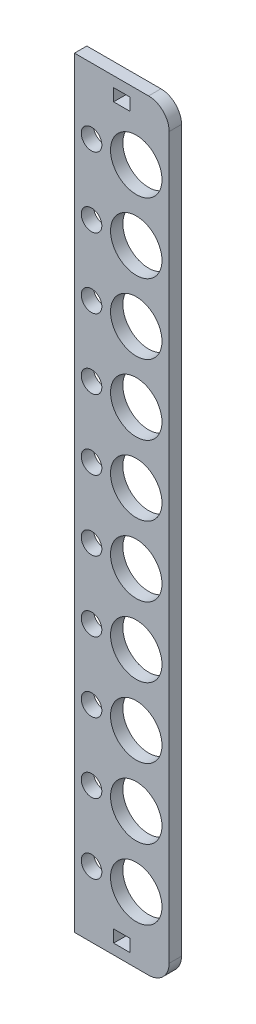
SolidWorks part; units mm, degrees
ref_plane "Plan de face" through (0, 0, 0) normal (0, 0, 1) x (1, 0, 0)
ref_plane "Plan de dessus" through (0, 0, 0) normal (0, 1, 0) x (1, 0, 0)
ref_plane "Plan de droite" through (0, 0, 0) normal (1, 0, 0) x (0, 0, -1)
sketch "Esquisse1" plane through (0, 0, 0) normal (0, 0, 1) x (1, 0, 0)
  line L0 (0, 185) -> (46, 185) construction
  line L1 (0, 0) -> (46, 0)
  line L2 (0, 0) -> (0, 370)
  line L3 (0, 370) -> (46, 370)
  line L4 (46, 0) -> (46, 370)
  line L5 (19, 5) -> (27, 5)
  line L6 (19, 5) -> (19, 11)
  line L7 (19, 11) -> (27, 11)
  line L8 (27, 5) -> (27, 11)
  line L9 (27, 365) -> (27, 359)
  line L10 (19, 359) -> (27, 359)
  line L11 (19, 365) -> (19, 359)
  line L12 (19, 365) -> (27, 365)
  dimension "D1" = 370
  dimension "D2" = 46
  dimension "D3" = 8
  dimension "D4" = 6
  dimension "D5" = 5
  dimension "D6" = 19
extrude "Boss.-Extru.1" add sketch "Esquisse1" along normal blind 6
sketch "Esquisse2" plane through (0, 0, 6) normal (0, 0, 1) x (1, 0, 0)
  line L0 (0, 370) -> (0, 0) construction
  line L1 (0, 0) -> (46, 0) construction
  line L2 (46, 0) -> (46, 370) construction
  line L3 (46, 370) -> (0, 370) construction
  circle A0 centre (30, 32) radius 12.5
  circle A1 centre (30, 66) radius 12.5
  circle A2 centre (30, 100) radius 12.5
  circle A3 centre (30, 134) radius 12.5
  circle A4 centre (30, 168) radius 12.5
  circle A5 centre (30, 202) radius 12.5
  circle A6 centre (30, 236) radius 12.5
  circle A7 centre (30, 270) radius 12.5
  circle A8 centre (30, 304) radius 12.5
  circle A9 centre (8.2811, 338) radius 5
  circle A10 centre (8.2811, 304) radius 5
  circle A11 centre (8.2811, 270) radius 5
  circle A12 centre (8.2811, 236) radius 5
  circle A13 centre (8.2811, 202) radius 5
  circle A14 centre (8.2811, 168) radius 5
  circle A15 centre (8.2811, 134) radius 5
  circle A16 centre (8.2811, 100) radius 5
  circle A17 centre (8.2811, 66) radius 5
  circle A18 centre (30, 338) radius 12.5
  circle A19 centre (8.2811, 32) radius 5
  dimension "D1" = 25
  dimension "D2" = 30
  dimension "D4" = 32
  dimension "D5" = 32
  dimension "D6" = 10
  dimension "D8" = 32
  dimension "D9" = 32
  dimension "D10" = 16
  dimension "D3" = 10
  dimension "D7" = 10
extrude "Enlèv. mat.-Extru.1" cut sketch "Esquisse2" against normal blind 6
fillet "Congé1" radius 10 2 edges at (46, 0, 3) (46, 370, 3)
